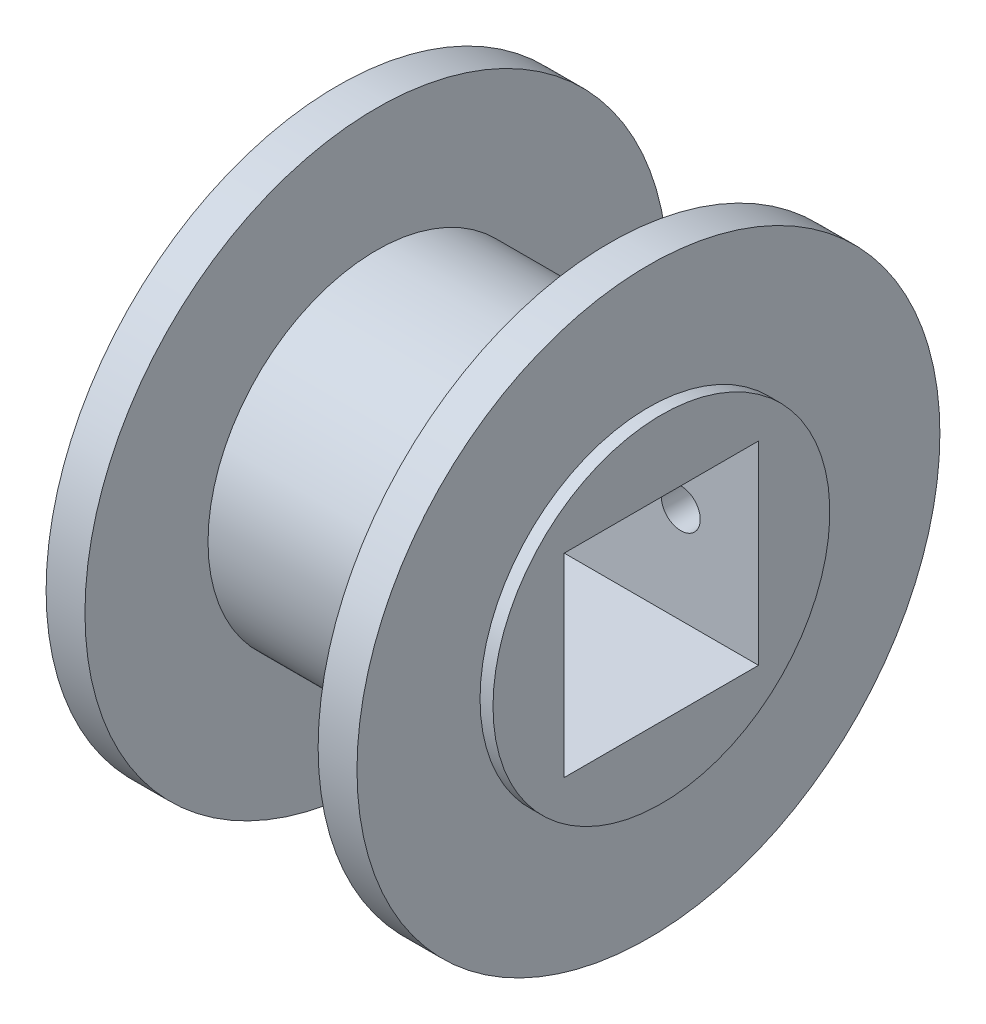
SolidWorks part; units mm, degrees
ref_plane "Piano frontale" through (0, 0, 0) normal (0, 0, 1) x (1, 0, 0)
ref_plane "Piano superiore" through (0, 0, 0) normal (0, 1, 0) x (1, 0, 0)
ref_plane "Piano destro" through (0, 0, 0) normal (1, 0, 0) x (0, 0, -1)
sketch "Schizzo1" plane through (0, 0, 0) normal (0, 0, 1) x (1, 0, 0)
  line L0 (-15.7092, 0) -> (19.4067, 0) construction
  line L1 (-13, 0) -> (13, 0)
  line L2 (13, 0) -> (13, 13)
  line L3 (13, 13) -> (12, 13)
  line L4 (12, 13) -> (12, 22.5)
  line L5 (12, 22.5) -> (9, 22.5)
  line L6 (9, 22.5) -> (9, 13)
  line L7 (9, 13) -> (-9, 13)
  line L8 (-9, 13) -> (-9, 22.5)
  line L9 (-9, 22.5) -> (-12, 22.5)
  line L10 (-12, 22.5) -> (-12, 13)
  line L11 (-12, 13) -> (-13, 13)
  line L12 (-13, 13) -> (-13, 0)
  dimension "D1" = 18
  dimension "D2" = 26
  dimension "D4" = 26
  dimension "D5" = 45
  dimension "D6" = 3
  dimension "D7" = 3
  dimension "D8" = 1
revolve "Rivoluzione1" add sketch "Schizzo1" angle 360 about L0
sketch "Schizzo2" plane through (-13, 0, 0) normal (-1, 0, 0) x (0, 0, 1)
  line L1 (7.5, -7.5) -> (-7.5, -7.5)
  line L2 (7.5, -7.5) -> (7.5, 7.5)
  line L3 (7.5, 7.5) -> (-7.5, 7.5)
  line L4 (-7.5, -7.5) -> (-7.5, 7.5)
  line L5 (7.5, -7.5) -> (-7.5, 7.5) construction
  line L6 (7.5, 7.5) -> (-7.5, -7.5) construction
  point P0 (0, 0)
  dimension "D1" = 15
  dimension "D2" = 15
extrude "Taglio-Estrusione1" cut sketch "Schizzo2" against normal through all
sketch "Schizzo3" plane through (0, 0, 0) normal (0, 0, 1) x (1, 0, 0)
  line L0 (0, 0) -> (9.2054, 0) construction
  line L1 (13, -13) -> (13, 13) construction
  circle A0 centre (7, 0) radius 1.5
  dimension "D1" = 3
  dimension "D2" = 6
extrude "Taglio-Estrusione2" cut sketch "Schizzo3" against normal through all
